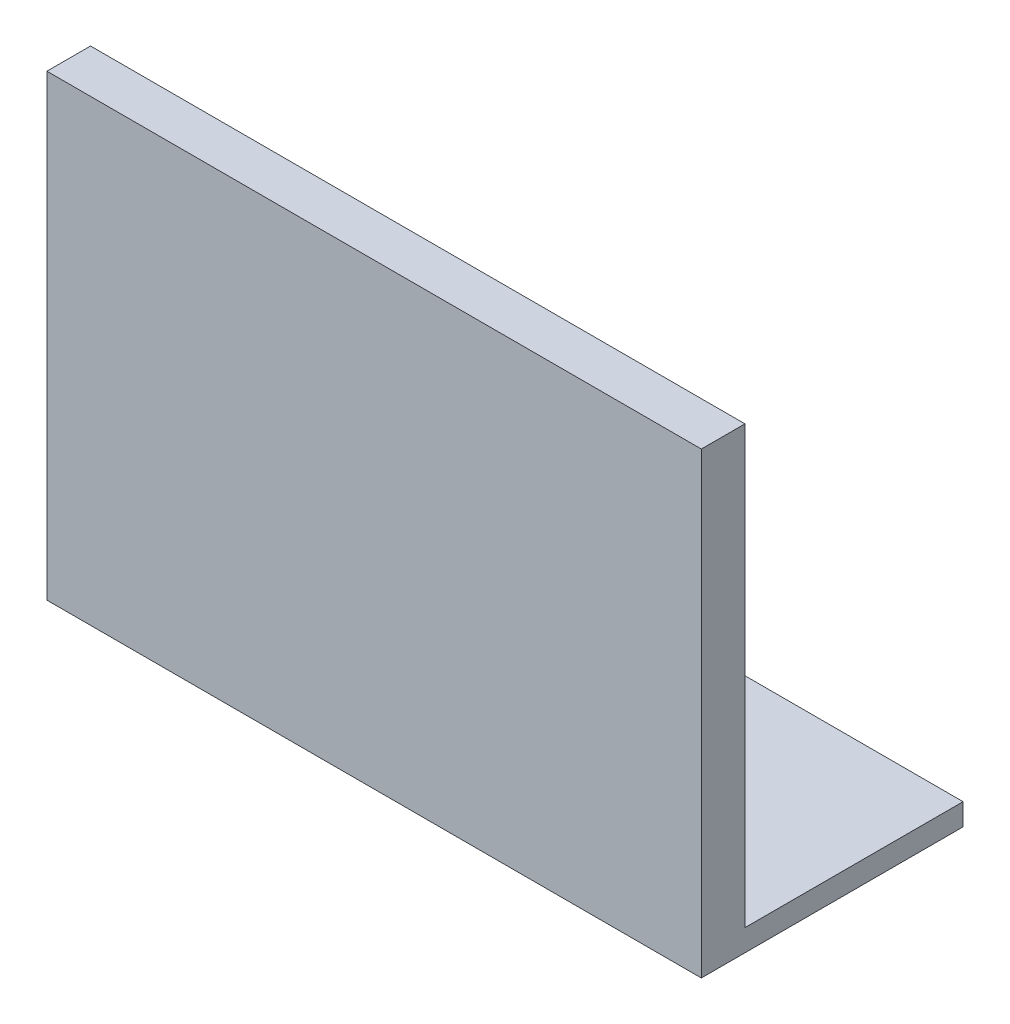
SolidWorks part; units mm, degrees
ref_plane "Front Plane" through (0, 0, 0) normal (0, 0, 1) x (1, 0, 0)
ref_plane "Top Plane" through (0, 0, 0) normal (0, 1, 0) x (1, 0, 0)
ref_plane "Right Plane" through (0, 0, 0) normal (1, 0, 0) x (0, 0, -1)
sketch "Sketch2" plane through (0, 0, 0) normal (0, 1, 0) x (1, 0, 0)
  line L1 (75, 30) -> (-75, 30)
  line L2 (75, 30) -> (75, -30)
  line L3 (75, -30) -> (-75, -30)
  line L4 (-75, 30) -> (-75, -30)
  line L5 (75, 30) -> (-75, -30) construction
  line L6 (75, -30) -> (-75, 30) construction
  point P0 (0, 0)
  dimension "D1" = 60
  dimension "D2" = 150
extrude "Boss-Extrude2" add sketch "Sketch2" along normal blind 5
sketch "Sketch3" plane through (0, 5, 0) normal (0, 1, 0) x (1, 0, 0)
  line L0 (75, -30) -> (75, 30) construction
  line L1 (-75, -30) -> (75, -30)
  line L2 (-75, -30) -> (-75, -20)
  line L3 (-75, -20) -> (75, -20)
  line L4 (75, -30) -> (75, -20)
  dimension "D1" = 10
extrude "Boss-Extrude3" add sketch "Sketch3" along normal blind 100
sketch "Sketch4" plane through (0, 5, 0) normal (0, 1, 0) x (1, 0, 0)
  line L0 (-75, 30) -> (-75, -20) construction
  line L1 (75, -20) -> (75, 30) construction
  line L2 (75, 30) -> (-75, 30) construction
  line L3 (75, -20) -> (-75, -20) construction
  circle A0 centre (-25, 15) radius 3.5
  circle A1 centre (25, 15) radius 3.5
  dimension "D1" = 50
  dimension "D2" = 7
  dimension "D3" = 50
  dimension "D4" = 7
  dimension "D5" = 35
  dimension "D6" = 15
extrude "Cut-Extrude1" cut sketch "Sketch4" against normal through all
sketch "Sketch6" plane through (0, 5, 0) normal (0, 1, 0) x (1, 0, 0)
  circle A0 centre (-25, 15) radius 5
  circle A1 centre (25, 15) radius 5
  dimension "D1" = 10
  dimension "D2" = 10
extrude "Cut-Extrude2" cut sketch "Sketch6" against normal blind 1
